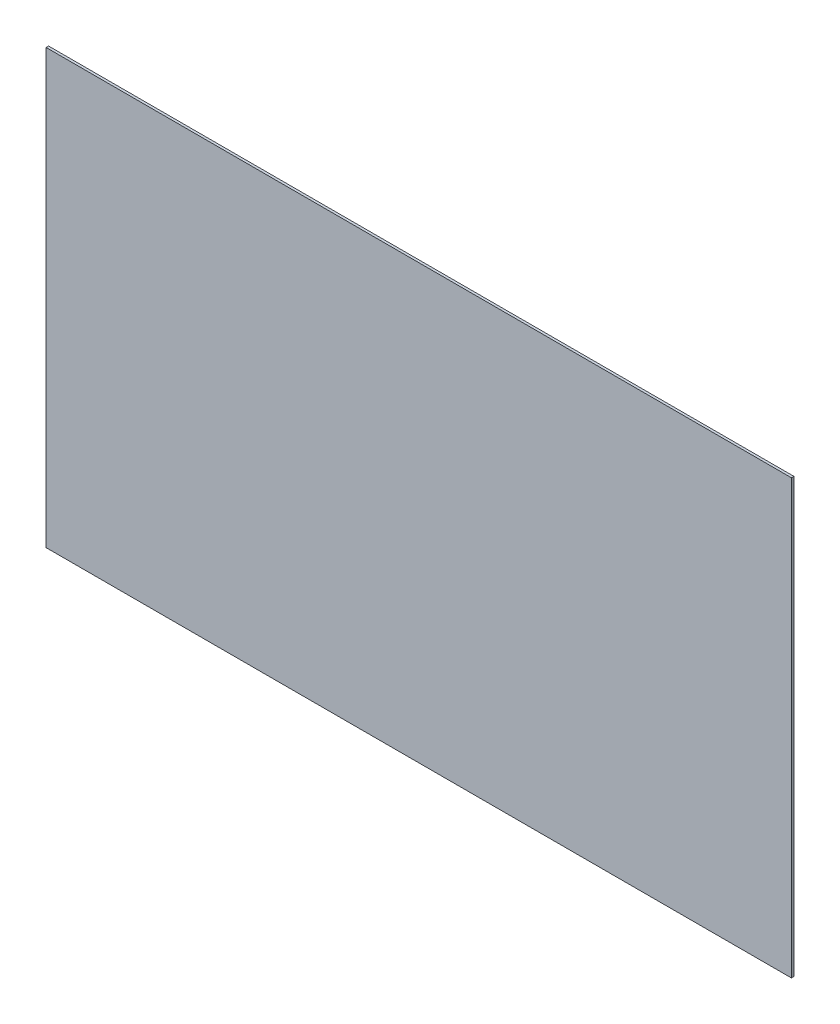
SolidWorks part; units mm, degrees
ref_plane "Alzado" through (0, 0, 0) normal (0, 0, 1) x (1, 0, 0)
ref_plane "Planta" through (0, 0, 0) normal (0, 1, 0) x (1, 0, 0)
ref_plane "Vista lateral" through (0, 0, 0) normal (1, 0, 0) x (0, 0, -1)
sketch "Sketch1" plane through (0, 0, 0) normal (0, 0, 1) x (1, 0, 0)
  line L1 (-600.5, -349) -> (600.5, -349)
  line L2 (-600.5, -349) -> (-600.5, 349)
  line L3 (-600.5, 349) -> (600.5, 349)
  line L4 (600.5, -349) -> (600.5, 349)
  line L5 (-600.5, -349) -> (600.5, 349) construction
  line L6 (-600.5, 349) -> (600.5, -349) construction
  point P0 (0, 0)
  dimension "D1" = 698
  dimension "D2" = 1201
extrude "Boss-Extrude1" add sketch "Sketch1" along normal blind 4
